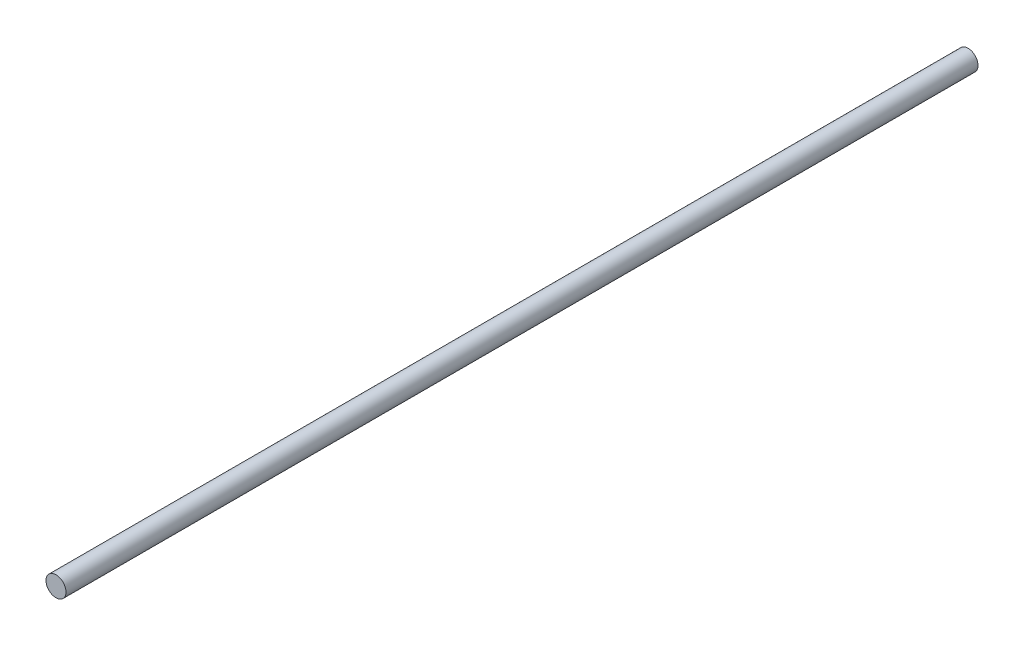
SolidWorks part; units mm, degrees
material "1.4000 (X6Cr13)"
ref_plane "Plan de face" through (0, 0, 0) normal (0, 0, 1) x (1, 0, 0)
ref_plane "Plan de dessus" through (0, 0, 0) normal (0, 1, 0) x (1, 0, 0)
ref_plane "Plan de droite" through (0, 0, 0) normal (1, 0, 0) x (0, 0, -1)
sketch "Esquisse1" plane through (0, 0, 0) normal (0, 0, 1) x (1, 0, 0)
  circle A0 centre (0, 0) radius 4
extrude "Boss.-Extru.1" add sketch "Esquisse1" along normal blind 365
ref_plane "SectionMiBarreY" through (0, 0, 182.5) normal (0, 0, -1) x (-1, 0, 0)
